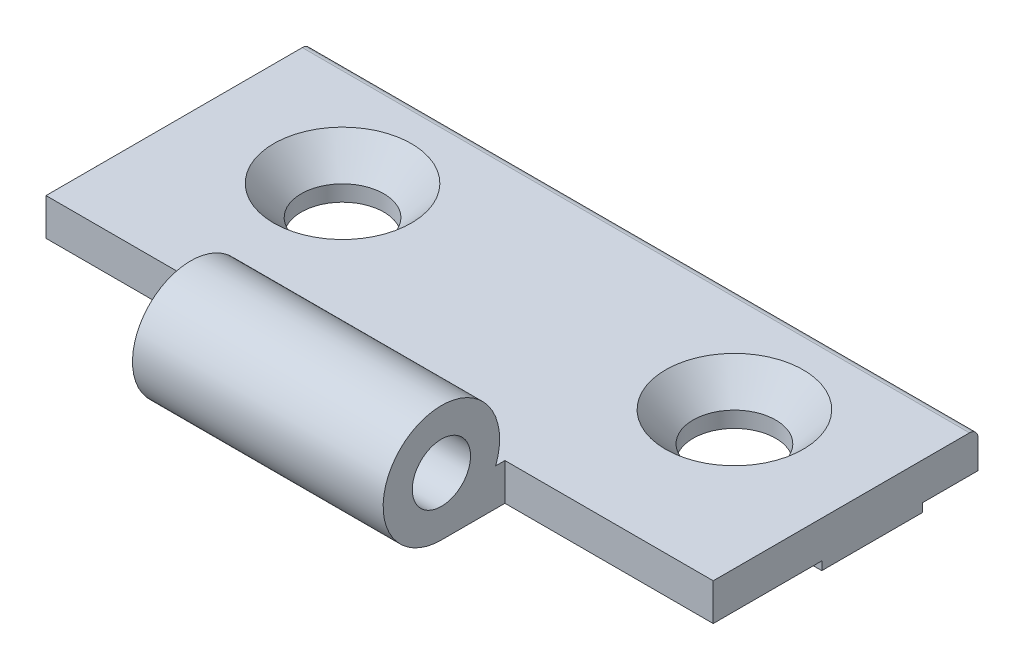
SolidWorks part; units mm, degrees
ref_plane "Front Plane" through (0, 0, 0) normal (0, 0, 1) x (1, 0, 0)
ref_plane "Top Plane" through (0, 0, 0) normal (0, 1, 0) x (1, 0, 0)
ref_plane "Right Plane" through (0, 0, 0) normal (1, 0, 0) x (0, 0, -1)
ref_plane "Plane1" through (11.8333, 0, 0) normal (1, 0, 0) x (0, 0, -1)
sketch "Sketch1" plane through (11.8333, 0, 0) normal (1, 0, 0) x (0, 0, -1)
  line L0 (31, 3.5) -> (5.1235, 3.5)
  line L1 (0, 0) -> (31, 0)
  line L2 (31, 0) -> (31, 3.5)
  arc A0 (5.1235, 3.5) -> (0, 0) centre (0, 5.5) ccw
extrude "Boss-Extrude1" add sketch "Sketch1" against normal blind 23.6667
sketch "Sketch2" plane through (-11.8333, 0, 0) normal (-1, 0, 0) x (0, 0, 1)
  line L0 (-31, 0) -> (-31, 3.5)
  line L1 (-31, 3.5) -> (-6, 3.5)
  line L2 (-6, 3.5) -> (-6, 0)
  line L3 (-6, 0) -> (-31, 0)
extrude "Boss-Extrude2" add sketch "Sketch2" along normal blind 19.6667
sketch "Sketch3" plane through (11.8333, 0, 0) normal (1, 0, 0) x (0, 0, -1)
  line L0 (31, 0) -> (6, 0)
  line L1 (6, 0) -> (6, 3.5)
  line L2 (6, 3.5) -> (31, 3.5)
  line L3 (31, 3.5) -> (31, 0)
extrude "Boss-Extrude3" add sketch "Sketch3" along normal blind 19.6667
sketch "Sketch4" plane through (0, 0, 0) normal (0, -1, 0) x (1, 0, 0)
  line L0 (-31.5, -31) -> (-31.5, -16.25)
  line L1 (-31.5, -16.25) -> (31.5, -16.25)
  line L2 (31.5, -16.25) -> (31.5, -31)
  line L3 (31.5, -31) -> (-31.5, -31)
extrude "Boss-Extrude4" add sketch "Sketch4" along normal blind 0.8
sketch "Sketch5" plane through (31.5, 0, 0) normal (1, 0, 0) x (0, 0, -1)
  line L0 (31, 0) -> (25.75, 0)
  line L1 (25.75, 0) -> (25.75, -0.8)
  line L2 (25.75, -0.8) -> (31, -0.8)
  line L3 (31, -0.8) -> (31, 0)
extrude "Cut-Extrude1" cut sketch "Sketch5" against normal through all
hole_wizard "#10 Clearance Hole1" positions "Sketch7" profile "Sketch6" hole size "#10" standard "ANSI Inch"
sketch "Sketch7" plane through (-11.8333, 0, 0) normal (-1, 0, 0) x (0, 0, 1)
  point P0 (0, 5.5)
sketch "Sketch6" plane through (-11.8333, 5.5, 0) normal (0, 1, 0) x (0, 0, 1)
  line L0 (0, 0) -> (0, 43.3333)
  line L1 (0, 43.3333) -> (2.75, 43.3333)
  line L2 (2.75, 43.3333) -> (2.75, 0)
  line L5 (2.75, 0) -> (0, 0)
  line L11 (0, -6.35) -> (0, 107.95) construction
  dimension "Thru Hole Dia." = 5.5
  dimension "Thru Hole Depth" = 43.3333
hole_wizard "Hole1" positions "Sketch9" profile "Sketch8" legacy
sketch "Sketch9" plane through (0, 3.5, 0) normal (0, 1, 0) x (1, 0, 0)
  point P0 (-18.5, 21)
  point P1 (18.5, 21)
sketch "Sketch8" plane through (-18.5, 3.5, -21) normal (1, 0, 0) x (0, 0, 1)
  line L0 (0, 0) -> (0, 4.3)
  line L1 (0, 4.3) -> (3.9, 4.3)
  line L2 (3.9, 4.3) -> (3.9, 2.8)
  line L3 (3.9, 2.8) -> (6.5, 0)
  line L4 (6.5, 0) -> (0, 0)
  line L5 (0, -6.4453) -> (0, 115.525) construction
  line L6 (-3.9, 2.8) -> (-6.5, 0) construction
  dimension "Diameter" = 7.8
  dimension "Depth" = 4.3
  dimension "C-Sink Angle" = 85.758
  dimension "C-Sink Diameter" = 13
fillet "Fillet1" radius 0.8 1 edges at (0, 3.5, -31)
scale "Scale1" scale about centroid uniform scaling yes scale factor 0.3333
